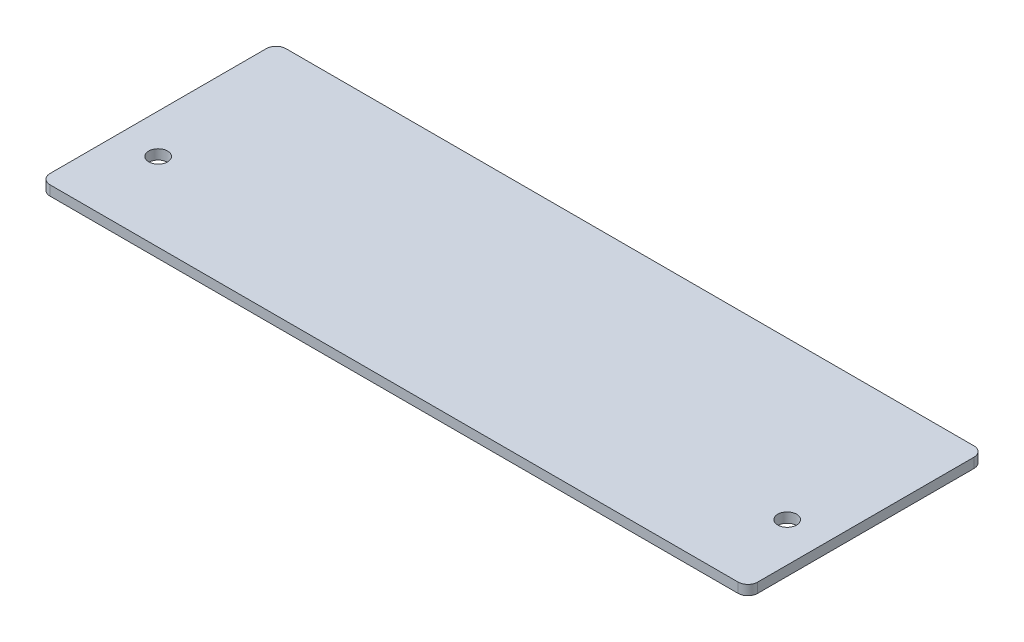
SolidWorks part; units mm, degrees
material "Custom Plastic"
ref_plane "Front" through (0, 0, 0) normal (0, 0, 1) x (1, 0, 0)
ref_plane "Top" through (0, 0, 0) normal (0, 1, 0) x (1, 0, 0)
ref_plane "Right" through (0, 0, 0) normal (1, 0, 0) x (0, 0, -1)
sketch "Sketch1" plane through (0, 0, 0) normal (0, 1, 0) x (1, 0, 0)
  line L9 (114.3, -38.1) -> (-114.3, -38.1)
  line L10 (114.3, -38.1) -> (114.3, 38.1)
  line L11 (114.3, 38.1) -> (-114.3, 38.1)
  line L12 (-114.3, -38.1) -> (-114.3, 38.1)
  line L13 (114.3, -38.1) -> (-114.3, 38.1) construction
  line L14 (114.3, 38.1) -> (-114.3, -38.1) construction
  point P0 (0, 0)
  dimension "D1" = 76.2
  dimension "D2" = 228.6
extrude "Boss-Extrude1" add sketch "Sketch1" along normal blind 3.175
sketch "Sketch2" plane through (0, 3.175, 0) normal (0, 1, 0) x (1, 0, 0)
  line L0 (-114.3, -12.7) -> (114.3, -12.7) construction
  line L1 (-114.3, 38.1) -> (-114.3, -38.1) construction
  line L2 (114.3, -38.1) -> (114.3, 38.1) construction
  line L3 (-114.3, -38.1) -> (114.3, -38.1) construction
  line L4 (0, 38.1) -> (0, -38.1) construction
  line L5 (114.3, 38.1) -> (-114.3, 38.1) construction
  circle A0 centre (-101.6, -12.7) radius 3.048
  circle A1 centre (101.6, -12.7) radius 3.048
  dimension "D2" = 6.096
  dimension "D1" = 25.4
  dimension "D3" = 101.6
extrude "Cut-Extrude1" cut sketch "Sketch2" against normal blind 10
fillet "Fillet1" radius 3.175 4 edges at (-114.3, 1.5875, -38.1) (114.3, 1.5875, 38.1) (-114.3, 1.5875, 38.1) (114.3, 1.5875, -38.1)
sketch "Sketch3" plane through (0, 0, 0) normal (0, -1, 0) x (1, 0, 0)
  line L0 (-1079.818, -50.8) -> (48920.182, -50.8) construction
  line L1 (-127, -1010.5406) -> (-127, 48989.4594) construction
  line L2 (127, -1021.6185) -> (127, 48978.3815) construction
  line L3 (111.125, -38.1) -> (-111.125, -38.1) construction
  line L4 (-114.3, -34.925) -> (-114.3, 34.925) construction
  line L5 (114.3, 34.925) -> (114.3, -34.925) construction
  point P5 (-127, -50.8)
  point P7 (127, -50.8)
  dimension "D1" = 12.7
  dimension "D2" = 12.7
  dimension "D3" = 12.7
